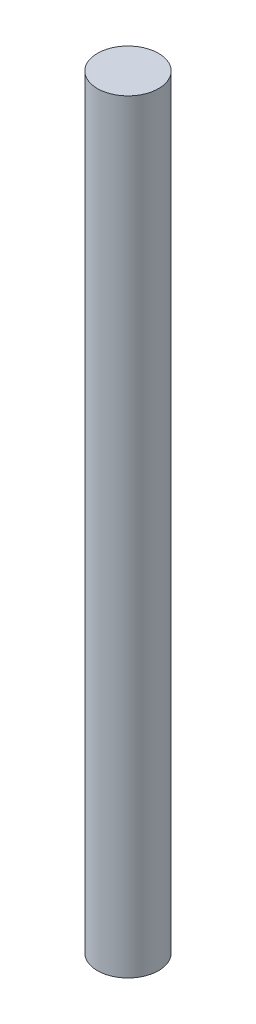
SolidWorks part; units mm, degrees
ref_plane "前视基准面" through (0, 0, 0) normal (0, 0, 1) x (1, 0, 0)
ref_plane "上视基准面" through (0, 0, 0) normal (0, 1, 0) x (1, 0, 0)
ref_plane "右视基准面" through (0, 0, 0) normal (1, 0, 0) x (0, 0, -1)
other "Configuration Table"
sketch "草图1" plane through (0, 0, 0) normal (0, 1, 0) x (1, 0, 0)
  circle A0 centre (0, 0) radius 4
  dimension "D1" = 8
extrude "凸台-拉伸1" add sketch "草图1" along normal blind 100
